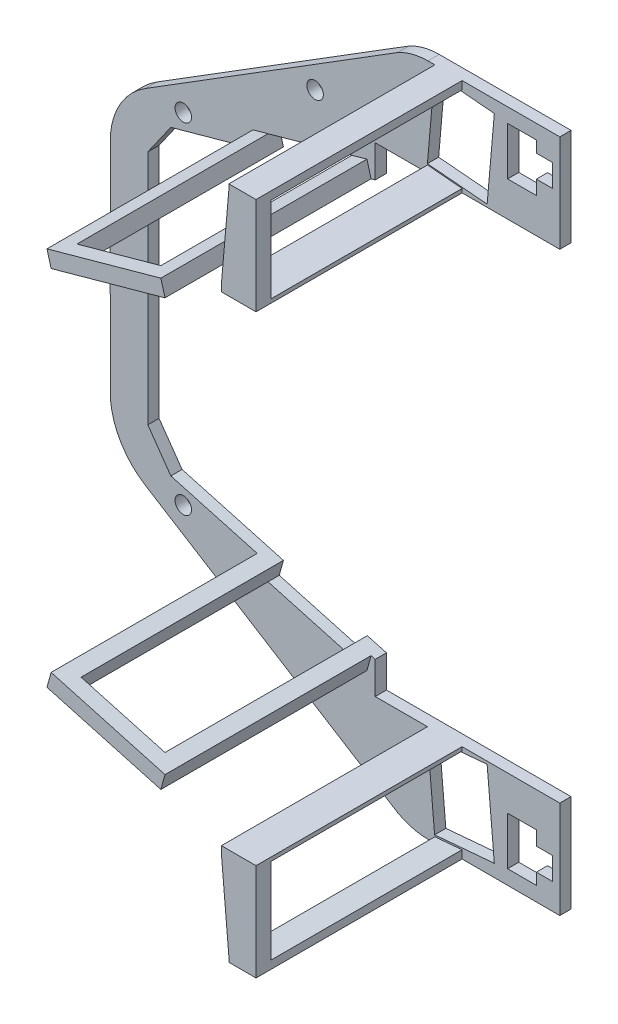
SolidWorks part; units mm, degrees
ref_plane "Front Plane" through (0, 0, 0) normal (0, 0, 1) x (1, 0, 0)
ref_plane "Top Plane" through (0, 0, 0) normal (0, 1, 0) x (1, 0, 0)
ref_plane "Right Plane" through (0, 0, 0) normal (1, 0, 0) x (0, 0, -1)
sketch "Sketch1" plane through (0, 0, 0) normal (0, 0, 1) x (1, 0, 0)
  line L0 (65, 15) -> (65, 5)
  line L1 (65, 5) -> (47.403, 5.0215)
  line L2 (46.938, 5.043) -> (47.868, 5) construction
  line L3 (43.379, 6.064) -> (9.7, 27.063)
  line L4 (5.042, 34.624) -> (5, 50)
  line L5 (65, 15) -> (65, 18)
  line L6 (65, 85) -> (65, 15) construction
  line L7 (65, 18) -> (40.3675, 18)
  line L8 (40.3675, 18) -> (40.3675, 22.2992)
  line L9 (40.3675, 22.2992) -> (37.8165, 23.0061)
  line L10 (10.021, 34.227) -> (10.021, 65.773)
  line L11 (65, 50) -> (5, 50) construction
  line L13 (65, 50) -> (10.021, 50) construction
  line L14 (65, 82) -> (40.3675, 82)
  line L15 (65, 85) -> (65, 82)
  line L16 (65, 85) -> (65, 95)
  line L17 (65, 95) -> (47.403, 94.9785)
  line L18 (40.3675, 82) -> (40.3675, 77.7008)
  line L19 (40.3675, 77.7008) -> (37.8165, 76.9939)
  line L20 (43.379, 93.936) -> (9.7, 72.937)
  line L21 (5.042, 65.376) -> (5, 50)
  line L22 (26.6181, 73.8907) -> (26.0635, 75.892)
  line L23 (26.0635, 75.892) -> (37.2619, 78.9952)
  line L24 (37.2619, 78.9952) -> (37.8165, 76.9939)
  line L25 (13.0928, 29.8574) -> (10.021, 34.227)
  line L26 (13.0928, 70.1426) -> (10.021, 65.773)
  line L27 (47.3336, 83.0656) -> (55.3032, 82.3683)
  line L28 (55.3032, 82.3683) -> (56.2619, 93.3265)
  line L29 (56.2619, 93.3265) -> (48.2923, 94.0237)
  line L30 (48.2923, 94.0237) -> (47.3336, 83.0656)
  line L31 (58.0329, 86.6518) -> (61.8647, 86.6518)
  line L32 (61.8647, 86.6518) -> (61.8647, 88.5446)
  line L33 (61.8647, 88.5446) -> (64.0046, 88.5446)
  line L34 (64.0046, 88.5446) -> (64.0046, 91.5464)
  line L35 (64.0046, 91.5464) -> (61.8649, 91.5464)
  line L40 (61.8649, 91.5464) -> (61.8649, 93.072)
  line L41 (61.8649, 93.072) -> (58.0329, 93.072)
  line L42 (58.0329, 93.072) -> (58.0329, 86.6518)
  line L43 (56.2619, 6.6735) -> (48.2923, 5.9763)
  line L44 (55.3032, 17.6317) -> (56.2619, 6.6735)
  line L45 (47.3336, 16.9344) -> (55.3032, 17.6317)
  line L46 (48.2923, 5.9763) -> (47.3336, 16.9344)
  line L47 (37.2619, 21.0048) -> (37.8165, 23.0061)
  line L48 (26.6181, 26.1093) -> (26.0635, 24.108)
  line L49 (26.0635, 24.108) -> (37.2619, 21.0048)
  line L50 (58.0329, 13.3482) -> (61.8647, 13.3482)
  line L51 (61.8647, 13.3482) -> (61.8647, 11.4554)
  line L52 (61.8647, 11.4554) -> (64.0046, 11.4554)
  line L53 (64.0046, 11.4554) -> (64.0046, 8.4536)
  line L54 (64.0046, 8.4536) -> (61.8649, 8.4536)
  line L55 (61.8649, 8.4536) -> (61.8649, 6.928)
  line L56 (61.8649, 6.928) -> (58.0329, 6.928)
  line L57 (58.0329, 6.928) -> (58.0329, 13.3482)
  line L58 (26.6181, 73.8907) -> (13.0928, 70.1426)
  line L59 (26.6181, 26.1093) -> (13.0928, 29.8574)
  arc A0 (47.403, 5.0215) -> (43.379, 6.064) centre (47.4132, 13.3482) cw
  arc A1 (9.7, 27.063) -> (5.042, 34.624) centre (14.9798, 35.5309) cw
  circle A2 centre (14.76, 27.32) radius 1.1 construction
  arc A3 (47.403, 94.9785) -> (43.379, 93.936) centre (47.4132, 86.6518) ccw
  arc A4 (9.7, 72.937) -> (5.042, 65.376) centre (14.9798, 64.4691) ccw
  circle A5 centre (32.343, 84.089) radius 1.1
  circle A6 centre (14.76, 72.68) radius 1.1
  circle A7 centre (14.76, 27.32) radius 1.1
  circle A8 centre (32.343, 15.911) radius 1.1
  point P15 (5.021, 42.312)
  point P44 (10.021, 50)
  dimension "D2" = 5
  dimension "D3" = 2
  dimension "D1" = 3
extrude "Boss-Extrude1" add sketch "Sketch1" along normal blind 1.5
sketch "Sketch2" plane through (0, 0, 1.5) normal (0, 0, 1) x (1, 0, 0)
  line L0 (26.6181, 26.1093) -> (26.0635, 24.108)
  line L3 (26.6181, 26.1093) -> (13.0928, 29.8574) construction
  line L4 (24.6181, 26.6636) -> (26.6181, 26.1093)
  line L5 (26.0635, 24.108) -> (24.0635, 24.6622)
  line L6 (24.0635, 24.6622) -> (24.6181, 26.6636)
  line L7 (37.2619, 21.0048) -> (37.8165, 23.0061)
  line L12 (37.8165, 23.0061) -> (39.8165, 22.4519)
  line L13 (40.3675, 22.2992) -> (37.8165, 23.0061) construction
  line L14 (39.8165, 22.4519) -> (39.2619, 20.4506)
  line L15 (39.2619, 20.4506) -> (37.2619, 21.0048)
  line L16 (5, 50) -> (65, 50) construction
  line L18 (65, 85) -> (65, 15) construction
  line L19 (39.8165, 77.5481) -> (39.2619, 79.5494)
  line L20 (37.8165, 76.9939) -> (39.8165, 77.5481)
  line L21 (37.2619, 78.9952) -> (37.8165, 76.9939)
  line L22 (39.2619, 79.5494) -> (37.2619, 78.9952)
  line L23 (26.0635, 75.892) -> (24.0635, 75.3378)
  line L24 (26.6181, 73.8907) -> (26.0635, 75.892)
  line L25 (24.6181, 73.3364) -> (26.6181, 73.8907)
  line L26 (24.0635, 75.3378) -> (24.6181, 73.3364)
  line L27 (47.3403, 18) -> (51.9624, 18)
  line L28 (65, 18) -> (40.3675, 18) construction
  line L31 (47.3403, 18) -> (47.3403, 17.0838)
  line L32 (47.3403, 17.0838) -> (51.9624, 17.4882)
  line L33 (51.9624, 17.4882) -> (51.9624, 18)
  line L34 (48.3302, 5.77) -> (51.9624, 6.0878)
  line L35 (51.9624, 6.0878) -> (51.9624, 5.0159)
  line L36 (47.403, 5.0215) -> (65, 5) construction
  line L37 (51.9624, 5.0159) -> (48.3302, 5.0204)
  line L38 (48.3302, 5.0204) -> (48.3302, 5.5519)
  line L39 (48.3302, 5.5519) -> (48.3302, 5.77)
  line L40 (48.3302, 94.9796) -> (48.3302, 94.4481)
  line L41 (51.9624, 94.9841) -> (48.3302, 94.9796)
  line L42 (51.9624, 93.9122) -> (51.9624, 94.9841)
  line L43 (48.3302, 94.23) -> (51.9624, 93.9122)
  line L44 (48.3302, 94.4481) -> (48.3302, 94.23)
  line L45 (47.3403, 82.9162) -> (51.9624, 82.5118)
  line L46 (47.3403, 82) -> (47.3403, 82.9162)
  line L47 (47.3403, 82) -> (51.9624, 82)
  line L48 (51.9624, 82.5118) -> (51.9624, 82)
  dimension "D1" = 2
  dimension "D2" = 2
extrude "Boss-Extrude2" add sketch "Sketch2" along normal blind 25.5
sketch "Sketch4" plane through (0, 0, 27) normal (0, 0, 1) x (1, 0, 0)
  line L0 (48.3302, 5.0204) -> (48.3302, 5.77)
  line L1 (48.3302, 5.77) -> (47.3403, 17.0838)
  line L2 (47.3403, 17.0838) -> (47.3403, 18)
  line L3 (47.3403, 18) -> (51.9624, 18)
  line L4 (51.9624, 18) -> (51.9624, 17.4882)
  line L5 (51.9624, 17.4882) -> (51.9624, 5.0159)
  line L6 (51.9624, 5.0159) -> (48.3302, 5.0204)
  line L7 (24.6181, 26.6636) -> (39.8165, 22.4519)
  line L8 (39.8165, 22.4519) -> (39.2619, 20.4506)
  line L9 (39.2619, 20.4506) -> (24.0635, 24.6622)
  line L10 (24.0635, 24.6622) -> (24.6181, 26.6636)
  line L11 (5, 50) -> (65, 50) construction
  line L12 (51.9624, 82.5118) -> (51.9624, 94.9841)
  line L13 (51.9624, 82) -> (51.9624, 82.5118)
  line L14 (47.3403, 82) -> (51.9624, 82)
  line L15 (47.3403, 82.9162) -> (47.3403, 82)
  line L16 (48.3302, 94.23) -> (47.3403, 82.9162)
  line L17 (48.3302, 94.9796) -> (48.3302, 94.23)
  line L18 (51.9624, 94.9841) -> (48.3302, 94.9796)
  line L19 (39.2619, 79.5494) -> (24.0635, 75.3378)
  line L20 (39.8165, 77.5481) -> (39.2619, 79.5494)
  line L21 (24.6181, 73.3364) -> (39.8165, 77.5481)
  line L22 (24.0635, 75.3378) -> (24.6181, 73.3364)
extrude "Boss-Extrude4" add sketch "Sketch4" along normal blind 2
